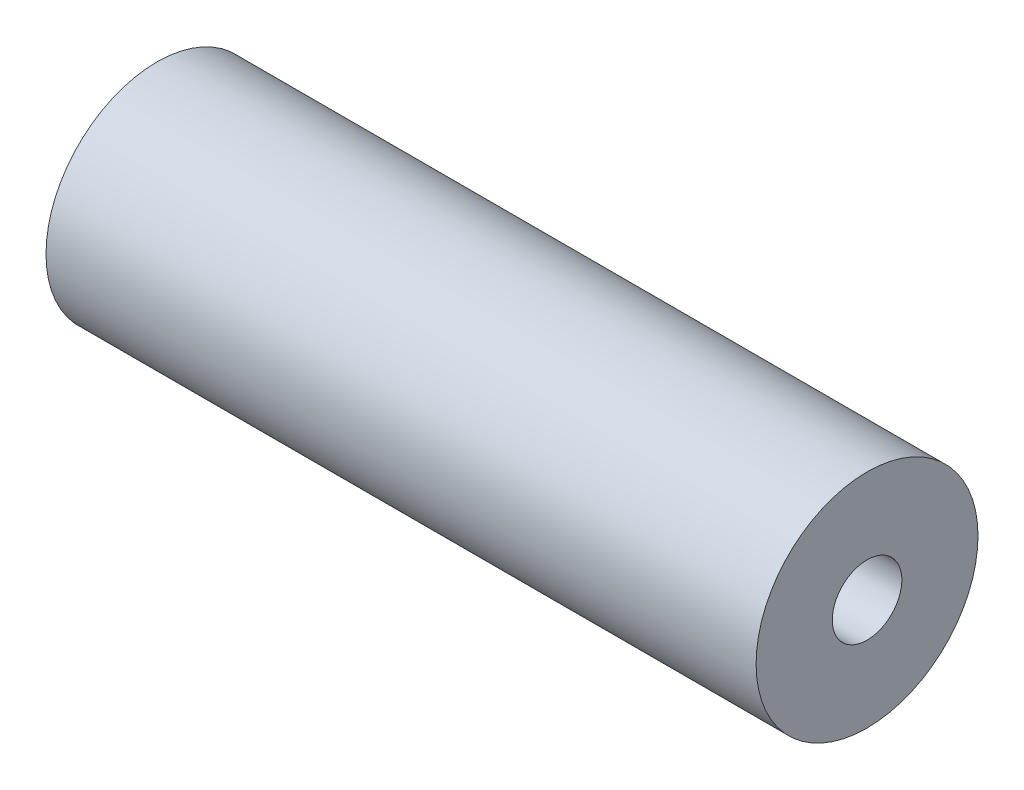
SolidWorks part; units mm, degrees
material "6061-T6 (SS)"
ref_plane "Front Plane" through (0, 0, 0) normal (0, 0, 1) x (1, 0, 0)
ref_plane "Top Plane" through (0, 0, 0) normal (0, 1, 0) x (1, 0, 0)
ref_plane "Right Plane" through (0, 0, 0) normal (1, 0, 0) x (0, 0, -1)
sketch "Sketch1" plane through (0, 0, 0) normal (0, 1, 0) x (1, 0, 0)
  line L0 (-72.894, 0) -> (78.2697, 0) construction
  line L1 (-25.4, 7.9375) -> (-25.4, 2.4892)
  line L2 (-25.4, 7.9375) -> (25.4, 7.9375)
  line L3 (-25.4, 2.4892) -> (25.4, 2.4892)
  line L4 (25.4, 7.9375) -> (25.4, 2.4892)
  line L5 (0, 0) -> (0, 2.4892) construction
  dimension "D1" = 15.875
  dimension "D2" = 4.9784
  dimension "D3" = 50.8
revolve "Revolve1" add sketch "Sketch1" angle 360 about L0
